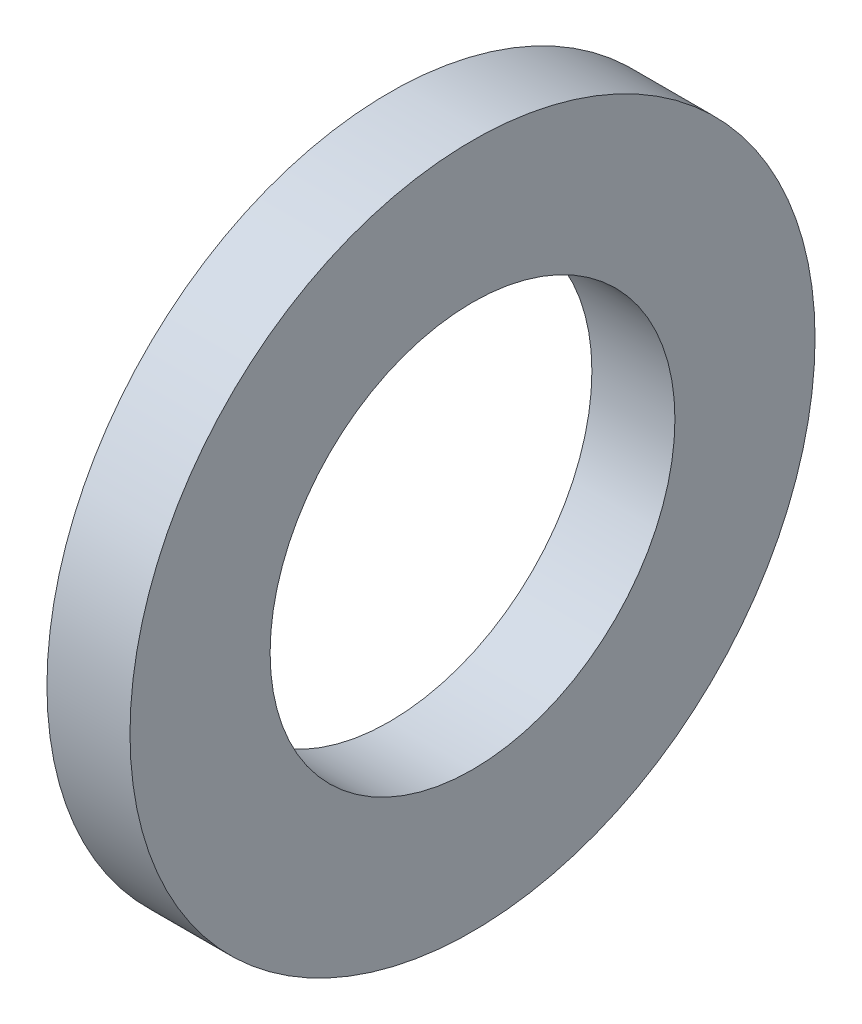
SolidWorks part; units mm, degrees
ref_plane "Plane1" through (0, 0, 0) normal (0, 0, 1) x (1, 0, 0)
ref_plane "Plane2" through (0, 0, 0) normal (0, 1, 0) x (1, 0, 0)
ref_plane "Plane3" through (0, 0, 0) normal (1, 0, 0) x (0, 0, -1)
sketch "Sketch1" plane through (0, 0, 0) normal (1, 0, 0) x (0, 0, -1)
  circle A0 centre (0, 0) radius 19.5
  circle A1 centre (0, 0) radius 33
  dimension "InsideDia" = 39
  dimension "OutsideDia" = 66
extrude "Base-Extrude" add sketch "Sketch1" along normal blind 8
